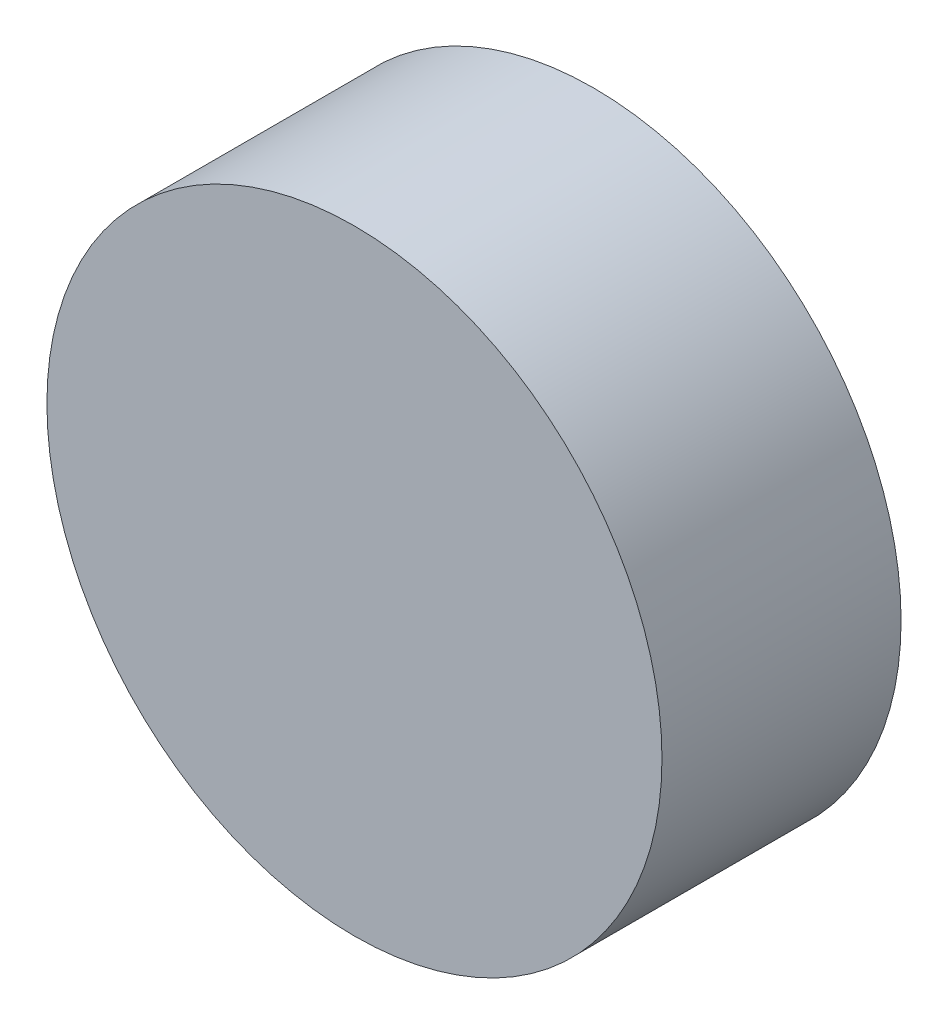
SolidWorks part; units mm, degrees
ref_plane "Front Plane" through (0, 0, 0) normal (0, 0, 1) x (1, 0, 0)
ref_plane "Top Plane" through (0, 0, 0) normal (0, 1, 0) x (1, 0, 0)
ref_plane "Right Plane" through (0, 0, 0) normal (1, 0, 0) x (0, 0, -1)
sketch "Sketch1" plane through (0, 0, 0) normal (0, 0, 1) x (1, 0, 0)
  circle A0 centre (51.9933, -18.0533) radius 12.862
extrude "Boss-Extrude1" add sketch "Sketch1" along normal blind 10
